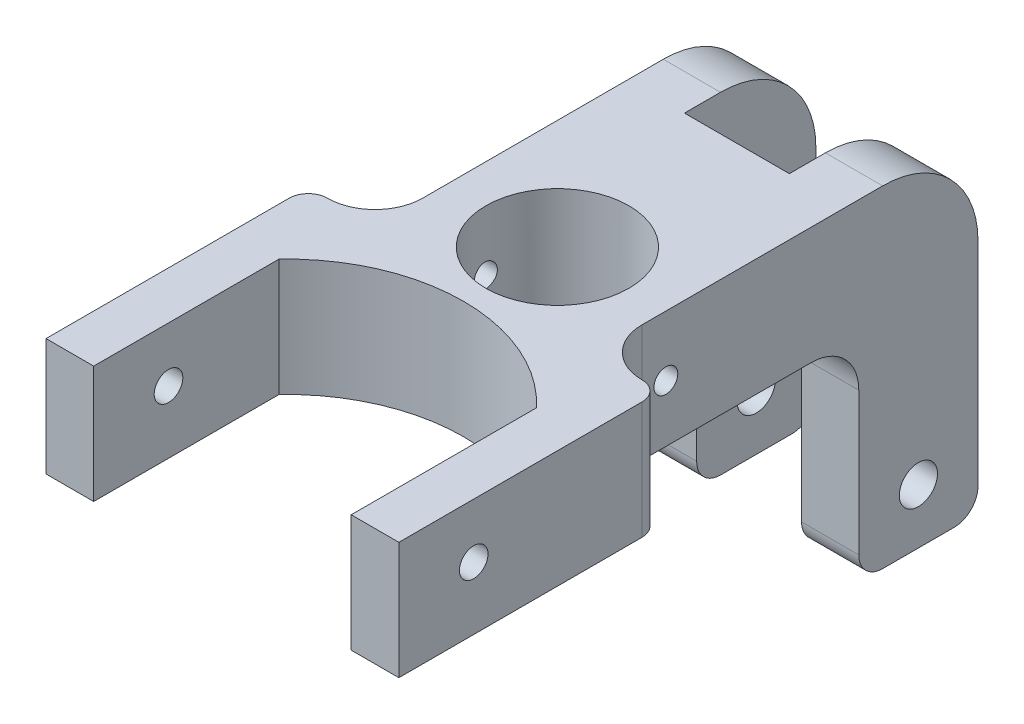
SolidWorks part; units mm, degrees
ref_plane "Спереди" through (0, 0, 0) normal (0, 0, 1) x (1, 0, 0)
ref_plane "Сверху" through (0, 0, 0) normal (0, 1, 0) x (1, 0, 0)
ref_plane "Справа" through (0, 0, 0) normal (1, 0, 0) x (0, 0, -1)
sketch "Эскиз1" plane through (0, 0, 0) normal (1, 0, 0) x (0, 0, -1)
  line L0 (3.6837, 0) -> (3.6837, -24.5969)
  line L1 (3.6837, -24.5969) -> (49.1322, -24.5969)
  line L3 (3.6837, 0) -> (64.1322, 0)
  line L7 (59.1322, -34.5969) -> (59.1322, -64.5182)
  line L8 (64.1322, -69.5182) -> (79.1322, -69.5182)
  line L9 (84.1322, -64.5182) -> (84.1322, -20)
  arc A0 (84.1322, -20) -> (64.1322, 0) centre (64.1322, -20) ccw
  arc A1 (59.1322, -34.5969) -> (49.1322, -24.5969) centre (49.1322, -34.5969) ccw
  arc A2 (64.1322, -69.5182) -> (59.1322, -64.5182) centre (64.1322, -64.5182) cw
  arc A3 (84.1322, -64.5182) -> (79.1322, -69.5182) centre (79.1322, -64.5182) cw
  dimension "D1" = 20
  dimension "D2" = 10
  dimension "D3" = 5
extrude "Вытянуть1" add sketch "Эскиз1" along normal blind 46 from offset 3
sketch "Эскиз2" plane through (0, 0, 0) normal (0, 1, 0) x (1, 0, 0)
  line L0 (20, 84.1322) -> (20, 104.5676) construction
  line L1 (9, 97.5814) -> (9, 56.5775)
  line L3 (31, 97.5814) -> (31, 56.5775)
  line L5 (9, 97.5814) -> (31, 97.5814)
  line L6 (31, 56.5775) -> (9, 56.5775)
  circle A0 centre (20, 18.9317) radius 15
  dimension "D1" = 30
  dimension "D2" = 11
extrude "Вытянуть2" cut sketch "Эскиз2" against normal mid plane 170
sketch "Эскиз3" plane through (0, 0, 0) normal (1, 0, 0) x (0, 0, -1)
  line L0 (5.675, 15.3538) -> (5.675, 28.3206) construction
  line L3 (31.675, 29.692) -> (31.675, 13.6083) construction
  line L6 (18.675, 32.1857) -> (18.675, 12.9849) construction
  circle A0 centre (71.6322, -58) radius 4
  circle A1 centre (18.675, -12.6282) radius 2.5
  dimension "D2" = 13
extrude "Вырез-Вытянуть1" cut sketch "Эскиз3" against normal mid plane 110
sketch "Эскиз4" plane through (0, 0, -3.6837) normal (0, 0, 1) x (1, 0, 0)
  line L0 (57.0034, -24.5969) -> (-16.9966, -24.5969)
  line L1 (57.0034, -24.5969) -> (57.0034, 0)
  line L2 (57.0034, 0) -> (-16.9966, 0)
  line L3 (-16.9966, 0) -> (-16.9966, -24.5969)
  line L4 (47.0034, -21.4606) -> (47.0034, -1.4606) construction
  line L6 (-6.9966, -1.4606) -> (-6.9966, -21.4606) construction
  dimension "D1" = 10
  dimension "D2" = 10
extrude "Вытянуть3" add sketch "Эскиз4" along normal blind 55
sketch "Эскиз6" plane through (0, 0, 0) normal (0, 1, 0) x (1, 0, 0)
  line L0 (47.0034, -53.7136) -> (47.0034, -12.467)
  line L2 (-6.9966, -12.467) -> (-6.9966, -53.7136)
  line L3 (-6.9966, -53.7136) -> (47.0034, -53.7136)
  arc A0 (47.0034, -12.467) -> (-6.9966, -12.467) centre (20.0034, -37.7653) ccw
extrude "Вырез-Вытянуть2" cut sketch "Эскиз6" along normal mid plane 100
fillet "Скругление2" radius 4 2 edges at (57.0034, -12.2984, -3.6837) (-16.9966, -12.2984, -3.6837)
sketch "Эскиз7" plane through (57.0034, 0, 0) normal (1, 0, 0) x (0, 0, -1)
  circle A0 centre (-35.6235, -11.4606) radius 3
extrude "Вырез-Вытянуть3" cut sketch "Эскиз7" against normal mid plane 180
fillet "Скругление3" radius 10 2 edges
sketch "Эскиз8" plane through (0, 0, 0) normal (0, 0, 1) x (1, 0, 0)
  line L0 (-16.9966, 0) -> (57.0034, -72.4866) construction
  line L1 (-16.9966, 0) -> (57.0034, 0) construction
  line L2 (-16.9966, 0) -> (-16.9966, -72.4866) construction
  line L3 (-16.9966, -72.4866) -> (57.0034, -72.4866) construction
  line L4 (57.0034, 0) -> (57.0034, -72.4866) construction
  line L5 (57.0034, 0) -> (-16.9966, -72.4866) construction
  circle A0 centre (20.0034, -36.2433) radius 50
